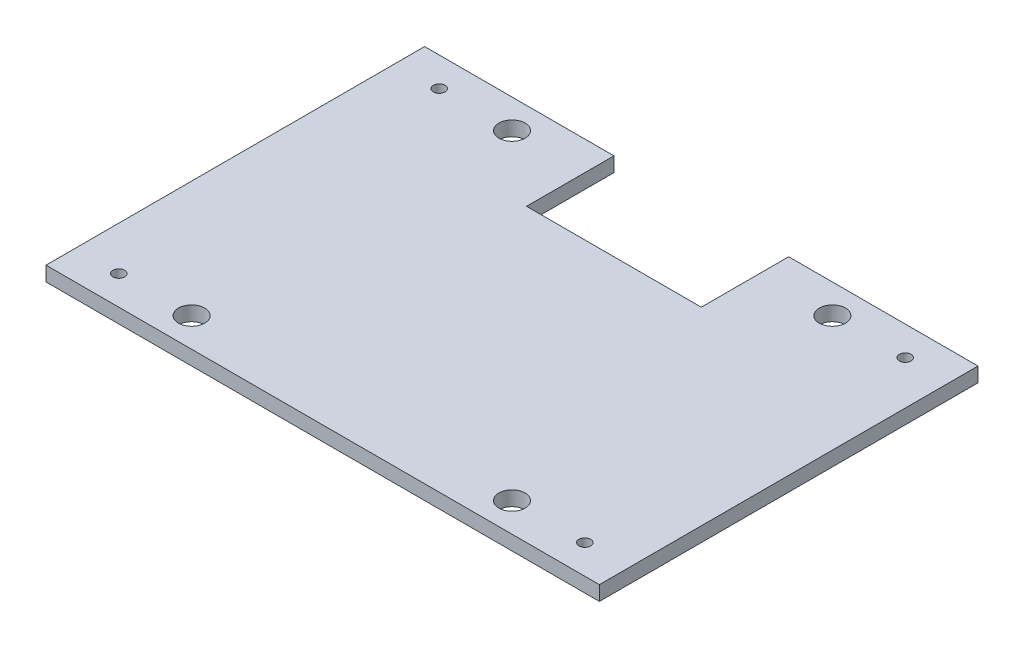
SolidWorks part; units mm, degrees
material "Thornel Mat VMA"
ref_plane "前视基准面" through (0, 0, 0) normal (0, 0, 1) x (1, 0, 0)
ref_plane "上视基准面" through (0, 0, 0) normal (0, 1, 0) x (1, 0, 0)
ref_plane "右视基准面" through (0, 0, 0) normal (1, 0, 0) x (0, 0, -1)
sketch "草图1" plane through (0, 0, 0) normal (0, 1, 0) x (1, 0, 0)
  line L0 (-78.175, 0) -> (88.7293, 0) construction
  line L1 (0, 82.8385) -> (0, -74.9842) construction
  line L2 (30, 65) -> (95, 65)
  line L3 (-95, 65) -> (-30, 65)
  line L4 (-95, 65) -> (-95, -65)
  line L5 (-95, -65) -> (95, -65)
  line L6 (95, 65) -> (95, -65)
  line L8 (-30, 65) -> (-30, 35)
  line L9 (-30, 35) -> (30, 35)
  line L10 (30, 65) -> (30, 35)
  circle A0 centre (-55, 55) radius 4.5
  circle A1 centre (55, 55) radius 4.5
  circle A2 centre (55, -55) radius 4.5
  circle A3 centre (-55, -55) radius 4.5
  circle A4 centre (-80, 55) radius 2
  circle A5 centre (-80, -55) radius 2
  circle A6 centre (80, -55) radius 2
  circle A7 centre (80, 55) radius 2
  dimension "D1" = 9
  dimension "D8" = 4
  dimension "D2" = 110
  dimension "D3" = 110
  dimension "D4" = 40
  dimension "D5" = 10
  dimension "D6" = 30
  dimension "D7" = 60
  dimension "D9" = 110
  dimension "D10" = 15
extrude "凸台-拉伸1" add sketch "草图1" along normal blind 5
